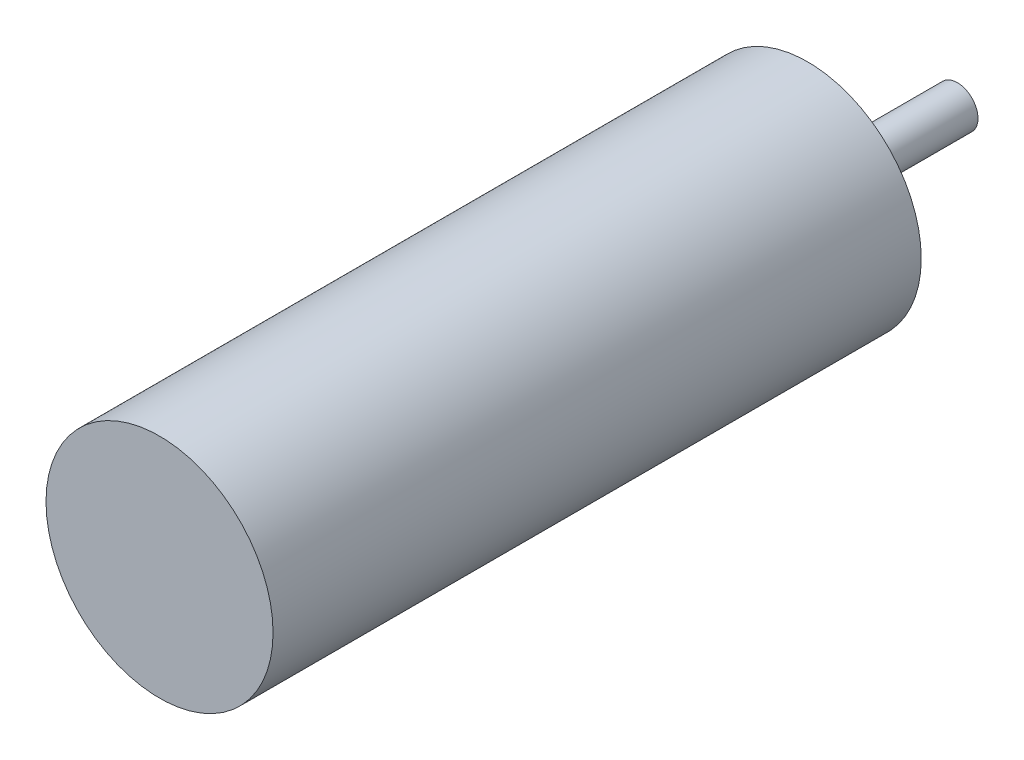
SolidWorks part; units mm, degrees
ref_plane "Front Plane" through (0, 0, 0) normal (0, 0, 1) x (1, 0, 0)
ref_plane "Top Plane" through (0, 0, 0) normal (0, 1, 0) x (1, 0, 0)
ref_plane "Right Plane" through (0, 0, 0) normal (1, 0, 0) x (0, 0, -1)
sketch "Sketch1" plane through (0, 0, 0) normal (0, 1, 0) x (1, 0, 0)
  line L0 (0, 0) -> (0, 22982.0904) construction
  line L1 (0, 0) -> (11, 0)
  line L2 (11, 0) -> (11, 62.8)
  line L3 (11, 62.8) -> (7, 62.8)
  line L4 (7, 62.8) -> (7, 65.3)
  line L5 (7, 65.3) -> (2, 65.3)
  line L6 (2, 65.3) -> (2, 77.3)
  line L7 (2, 77.3) -> (0, 77.3)
  line L8 (0, 77.3) -> (0, 0)
  point P7 (2, 85.8393)
  point P12 (0, 0.6267)
  point P13 (7, 67.1123)
  dimension "D1" = 22
  dimension "D2" = 14
  dimension "D3" = 4
  dimension "D4" = 62.8
  dimension "D5" = 2.5
  dimension "D6" = 12
revolve "Revolve1" add sketch "Sketch1" angle 360 about L0
sketch "Sketch2" plane through (0, 0, -62.8) normal (0, 0, -1) x (-1, 0, 0)
  line L0 (-0.875, 10.7531) -> (8.875, -6.1343) construction
  circle A0 centre (0, 9.2376) radius 1.75 construction
  circle A1 centre (8, -4.6188) radius 1.75 construction
  circle A2 centre (-8, -4.6188) radius 1.75 construction
  circle A3 centre (-8, -4.6188) radius 1
  circle A4 centre (0, 9.2376) radius 1
  circle A5 centre (8, -4.6188) radius 1
  point P9 (0, 0)
  dimension "D1" = 3.5
  dimension "D4" = 2
  dimension "D3" = 19.5
  dimension "D2" = 3
extrude "Cut-Extrude1" cut sketch "Sketch2" against normal blind 3
